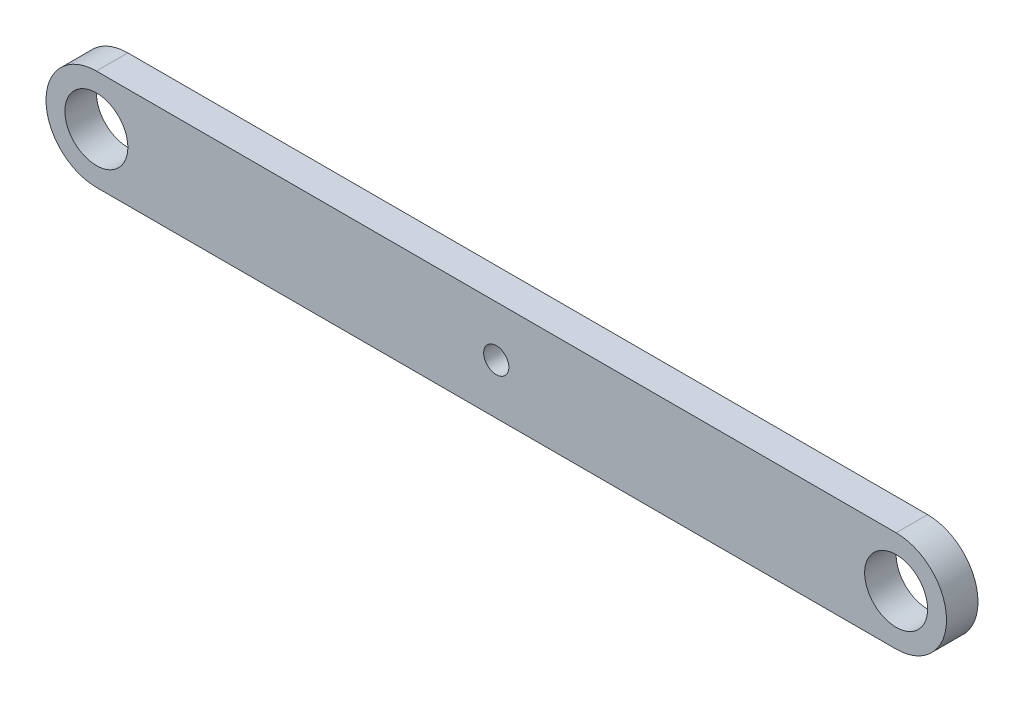
SolidWorks part; units mm, degrees
material "Stainless Steel (ferritic)"
ref_plane "Front Plane" through (0, 0, 0) normal (0, 0, 1) x (1, 0, 0)
ref_plane "Top Plane" through (0, 0, 0) normal (0, 1, 0) x (1, 0, 0)
ref_plane "Right Plane" through (0, 0, 0) normal (1, 0, 0) x (0, 0, -1)
sketch "Sketch1" plane through (0, 0, 0) normal (0, 0, 1) x (1, 0, 0)
  line L0 (-63.5, 0) -> (63.5, 0) construction
  line L1 (-63.5, 8) -> (63.5, 8)
  line L2 (-63.5, -8) -> (63.5, -8)
  arc A0 (-63.5, 8) -> (-63.5, -8) centre (-63.5, 0) ccw
  arc A1 (63.5, -8) -> (63.5, 8) centre (63.5, 0) ccw
  circle A2 centre (-63.5, 0) radius 5
  circle A3 centre (63.5, 0) radius 5
  circle A4 centre (0, 0) radius 2
  point P2 (0, 0)
  dimension "D2" = 10
  dimension "D3" = 3
  dimension "D4" = 4
  dimension "D1" = 127
extrude "Boss-Extrude1" add sketch "Sketch1" along normal mid plane 5
